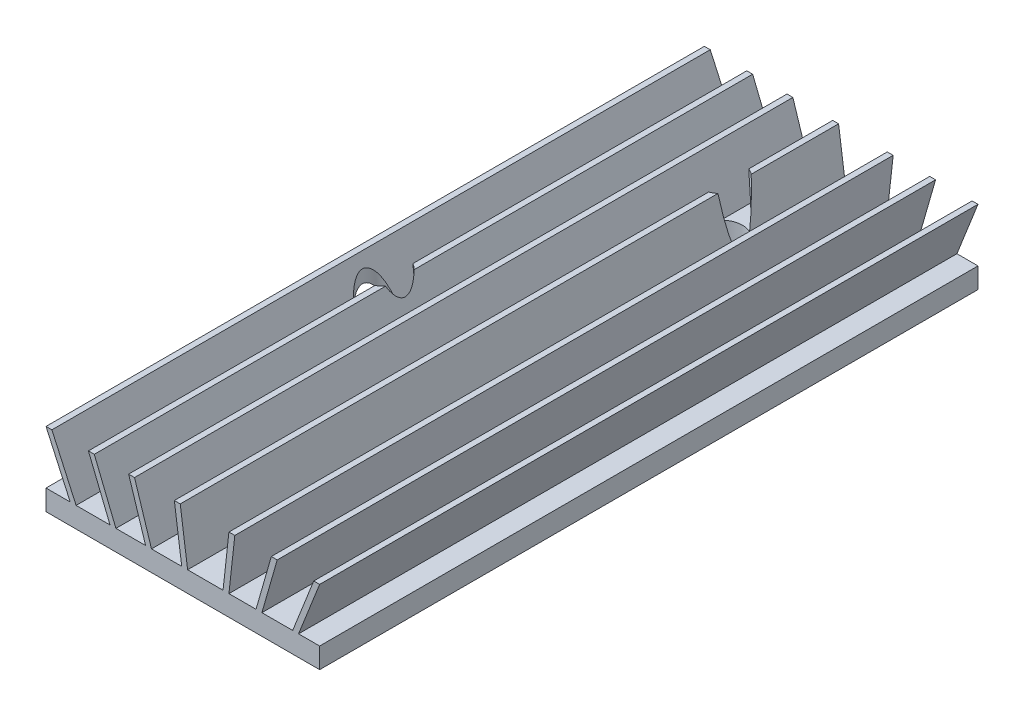
SolidWorks part; units mm, degrees
material "3003 Alloy"
ref_plane "Front Plane" through (0, 0, 0) normal (0, 0, 1) x (1, 0, 0)
ref_plane "Top Plane" through (0, 0, 0) normal (0, 1, 0) x (1, 0, 0)
ref_plane "Right Plane" through (0, 0, 0) normal (1, 0, 0) x (0, 0, -1)
sketch "Sketch1" plane through (0, 0, 0) normal (0, 0, 1) x (1, 0, 0)
  line L1 (0, 0) -> (25.4, 0)
  line L2 (0, 0) -> (0, 1.905)
  line L3 (0, 1.905) -> (25.4, 1.905)
  line L4 (25.4, 0) -> (25.4, 1.905)
  dimension "D1" = 1.905
  dimension "D2" = 25.4
extrude "Base" add sketch "Sketch1" along normal blind 61.1124
sketch "Sketch2" plane through (0, 0, 0) normal (0, 0, -1) x (-1, 0, 0)
  line L0 (-23.4443, 1.905) -> (-25.4, 6.858)
  line L1 (-25.4, 6.858) -> (-24.8538, 6.858)
  line L2 (-24.8538, 6.858) -> (-22.8981, 1.905)
  line L3 (-25.4, 1.905) -> (0, 1.905) construction
  line L4 (-23.4443, 1.905) -> (-22.8981, 1.905)
  line L5 (0, 0) -> (-25.4, 0) construction
  line L6 (-20.0405, 1.905) -> (-19.4944, 1.905)
  line L7 (-19.4944, 1.905) -> (-20.9168, 6.858)
  line L8 (-20.9168, 6.858) -> (-21.463, 6.858)
  line L9 (-21.463, 6.858) -> (-20.0405, 1.905)
  line L10 (-16.9798, 1.905) -> (-16.4337, 1.905)
  line L11 (0, 1.905) -> (0, 0) construction
  line L12 (-2.794, 1.905) -> (-2.2478, 1.905)
  line L13 (-2.2478, 1.905) -> (0, 6.858)
  line L14 (0, 6.858) -> (-0.5462, 6.858)
  line L15 (-0.5462, 6.858) -> (-2.794, 1.905)
  line L16 (-16.4337, 1.905) -> (-16.9798, 6.858)
  line L17 (-16.9798, 6.858) -> (-17.526, 6.858)
  line L18 (-17.526, 6.858) -> (-16.9798, 1.905)
  line L19 (-12.4588, 6.858) -> (-11.9126, 6.858)
  line L20 (-11.9126, 6.858) -> (-12.5983, 1.905)
  line L21 (-12.5983, 1.905) -> (-13.1444, 1.905)
  line L22 (-13.1444, 1.905) -> (-12.4588, 6.858)
  line L23 (-8.217, 6.858) -> (-7.6708, 6.858)
  line L24 (-7.6708, 6.858) -> (-9.2455, 1.905)
  line L25 (-9.2455, 1.905) -> (-9.7916, 1.905)
  line L26 (-9.7916, 1.905) -> (-8.217, 6.858)
  line L27 (-4.4832, 6.858) -> (-3.937, 6.858)
  line L28 (-3.937, 6.858) -> (-5.9435, 1.905)
  line L29 (-5.9435, 1.905) -> (-6.4896, 1.905)
  line L30 (-6.4896, 1.905) -> (-4.4832, 6.858)
  dimension "D1" = 0.508
  dimension "D2" = 6.858
  dimension "D3" = 2.5019
  dimension "D4" = 21.463
  dimension "D5" = 2.794
  dimension "D6" = 17.7927
  dimension "D7" = 14.732
  dimension "D8" = 17.526
  dimension "D9" = 10.8966
  dimension "D10" = 13.4874
  dimension "D11" = 7.5438
  dimension "D12" = 17.7292
  dimension "D13" = 4.2418
  dimension "D14" = 21.463
extrude "Fins" add sketch "Sketch2" against normal up to surface (61.1124 mm away) up to face at (12.7, 0.9525, 61.1124)
sketch "Sketch3" plane through (0, 1.905, 0) normal (0, 1, 0) x (1, 0, 0)
  line L4 (2.794, -61.1124) -> (5.9435, -61.1124)
  line L5 (5.9435, -61.1124) -> (5.9435, 0)
  line L6 (5.9435, 0) -> (2.794, 0)
  line L7 (2.794, 0) -> (2.794, -61.1124)
  line L8 (2.794, -61.1124) -> (5.9435, -61.1124)
  line L9 (5.9435, -61.1124) -> (5.9435, 0)
  line L10 (5.9435, 0) -> (2.794, 0)
  circle A0 centre (11.2, -9.655) radius 1.9939 construction
  circle A1 centre (11.2, -9.655) radius 1.9939
  circle A2 centre (3, -32.755) radius 1.9939 construction
  circle A3 centre (3, -32.755) radius 1.9939
  dimension "D1" = 0
extrude "Cut-Extrude1" cut sketch "Sketch3" against normal through all and the other way through all contours A1 | A3
